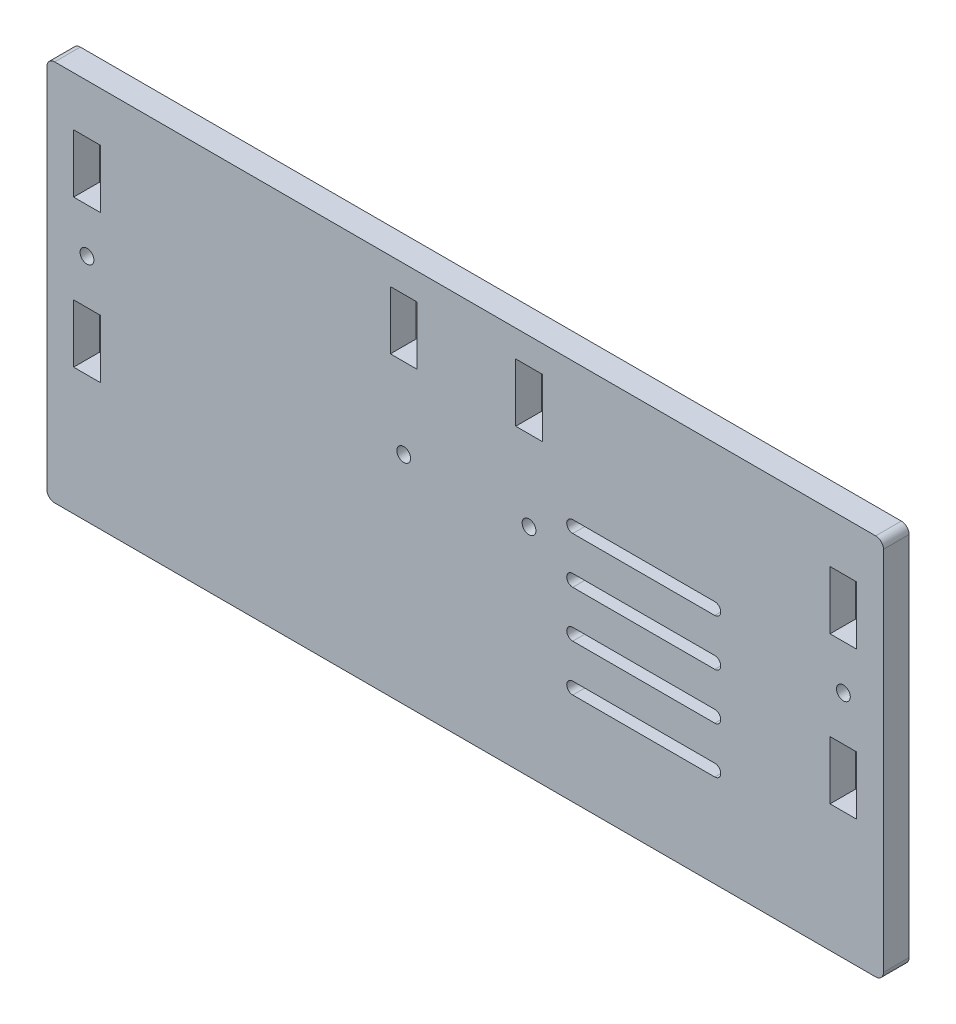
SolidWorks part; units mm, degrees
ref_plane "Front Plane" through (0, 0, 0) normal (0, 0, 1) x (1, 0, 0)
ref_plane "Top Plane" through (0, 0, 0) normal (0, 1, 0) x (1, 0, 0)
ref_plane "Right Plane" through (0, 0, 0) normal (1, 0, 0) x (0, 0, -1)
sketch "Model" plane through (0, 0, 0) normal (0, 0, 1) x (1, 0, 0)
  line L0 (135.3161, 59.8587) -> (171.868, 59.8587)
  line L1 (171.868, 62.9413) -> (135.3161, 62.9413)
  line L2 (135.3161, 47.8587) -> (171.868, 47.8587)
  line L3 (171.868, 50.9413) -> (135.3161, 50.9413)
  line L4 (95.25, 76.42) -> (95.25, 91.42)
  line L5 (95.25, 91.42) -> (88.39, 91.42)
  line L6 (88.39, 91.42) -> (88.39, 76.42)
  line L7 (88.39, 76.42) -> (95.25, 76.42)
  line L8 (127.51, 76.42) -> (127.51, 91.42)
  line L9 (127.51, 91.42) -> (120.65, 91.42)
  line L10 (120.65, 91.42) -> (120.65, 76.42)
  line L11 (120.65, 76.42) -> (127.51, 76.42)
  line L12 (208.4, 47.7) -> (201.54, 47.7)
  line L13 (201.54, 47.7) -> (201.54, 32.7)
  line L14 (201.54, 32.7) -> (208.4, 32.7)
  line L15 (208.4, 32.7) -> (208.4, 47.7)
  line L16 (208.4, 85.6) -> (201.54, 85.6)
  line L17 (201.54, 85.6) -> (201.54, 70.6)
  line L18 (201.54, 70.6) -> (208.4, 70.6)
  line L19 (208.4, 70.6) -> (208.4, 85.6)
  line L20 (13.74, 32.7) -> (13.74, 47.7)
  line L21 (13.74, 47.7) -> (6.88, 47.7)
  line L22 (6.88, 47.7) -> (6.88, 32.7)
  line L23 (6.88, 32.7) -> (13.74, 32.7)
  line L24 (13.74, 85.6) -> (6.88, 85.6)
  line L25 (6.88, 85.6) -> (6.88, 70.6)
  line L26 (6.88, 70.6) -> (13.74, 70.6)
  line L27 (13.74, 70.6) -> (13.74, 85.6)
  line L28 (171.868, 26.9413) -> (135.3161, 26.9413)
  line L29 (135.3161, 23.8587) -> (171.868, 23.8587)
  line L30 (171.868, 38.9413) -> (135.3161, 38.9413)
  line L31 (135.3161, 35.8587) -> (171.868, 35.8587)
  line L32 (213.28, 98.3) -> (2, 98.3)
  line L33 (215.28, 2) -> (215.28, 96.3)
  line L34 (2, 0) -> (213.28, 0)
  line L35 (0, 96.3) -> (0, 2)
  circle A0 centre (10.31, 59.15) radius 1.775
  circle A1 centre (204.97, 59.15) radius 1.775
  circle A2 centre (91.82, 55.71) radius 1.775
  circle A3 centre (124.08, 55.71) radius 1.775
  arc A4 (171.868, 59.8587) -> (171.868, 62.9413) centre (171.868, 61.4) ccw
  arc A5 (135.3161, 62.9413) -> (135.3161, 59.8587) centre (135.3161, 61.4) ccw
  arc A6 (171.868, 47.8587) -> (171.868, 50.9413) centre (171.868, 49.4) ccw
  arc A7 (135.3161, 50.9413) -> (135.3161, 47.8587) centre (135.3161, 49.4) ccw
  arc A8 (215.28, 96.3) -> (213.28, 98.3) centre (213.28, 96.3) ccw
  arc A9 (213.28, 0) -> (215.28, 2) centre (213.28, 2) ccw
  arc A10 (0, 2) -> (2, 0) centre (2, 2) ccw
  arc A11 (2, 98.3) -> (0, 96.3) centre (2, 96.3) ccw
  arc A12 (171.868, 23.8587) -> (171.868, 26.9413) centre (171.868, 25.4) ccw
  arc A13 (135.3161, 26.9413) -> (135.3161, 23.8587) centre (135.3161, 25.4) ccw
  arc A14 (171.868, 35.8587) -> (171.868, 38.9413) centre (171.868, 37.4) ccw
  arc A15 (135.3161, 38.9413) -> (135.3161, 35.8587) centre (135.3161, 37.4) ccw
extrude "Boss-Extrude1" add sketch "Model" along normal blind 6.6
